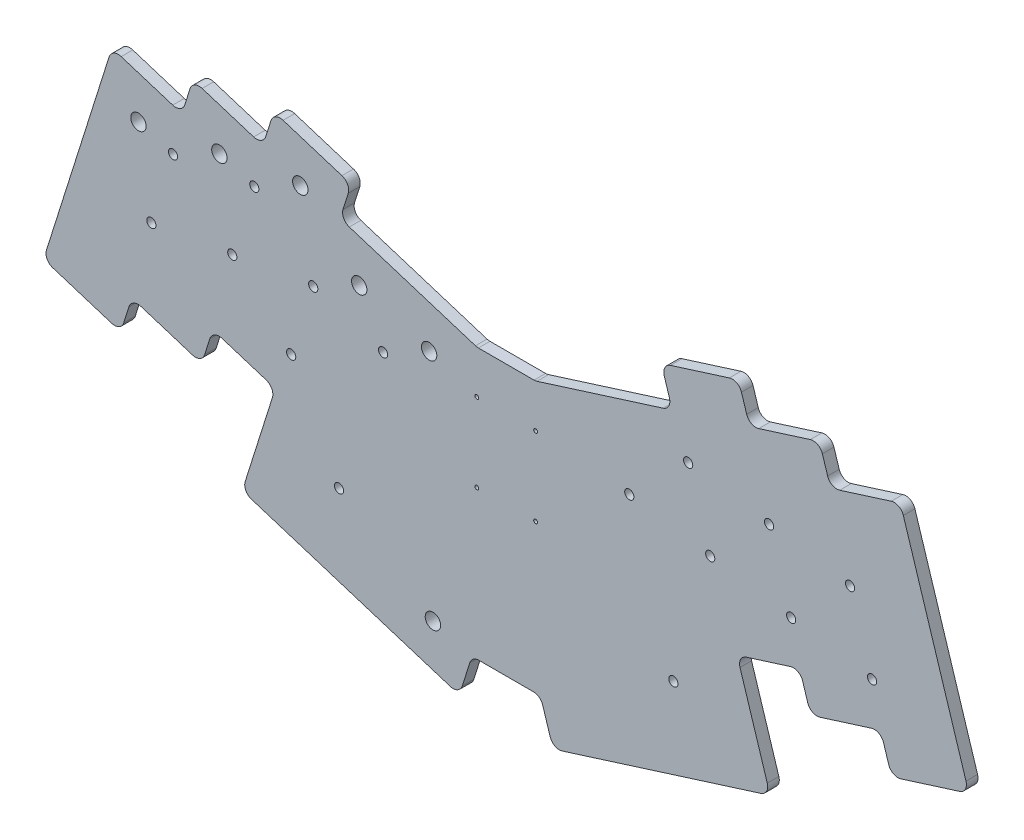
SolidWorks part; units mm, degrees
ref_plane "Front Plane" through (0, 0, 0) normal (0, 0, 1) x (1, 0, 0)
ref_plane "Top Plane" through (0, 0, 0) normal (0, 1, 0) x (1, 0, 0)
ref_plane "Right Plane" through (0, 0, 0) normal (1, 0, 0) x (0, 0, -1)
sketch "Sketch1" plane through (0, 0, 0) normal (0, 0, 1) x (1, 0, 0)
  line L68 (104.9688, -55.7943) -> (103.6157, -60.086)
  line L69 (100.4796, -61.7186) -> (87.1276, -57.5087)
  line L70 (83.9915, -59.1412) -> (82.6383, -63.4329)
  line L71 (79.5023, -65.0655) -> (66.1502, -60.8556)
  line L72 (63.0142, -62.4881) -> (46.7761, -113.9888)
  line L73 (48.4086, -117.1249) -> (63.6681, -121.9362)
  line L74 (66.8041, -120.3036) -> (68.1573, -116.0119)
  line L75 (71.2933, -114.3794) -> (84.6454, -118.5893)
  line L76 (87.7814, -116.9568) -> (89.1346, -112.665)
  line L77 (92.2707, -111.0325) -> (103.7153, -114.641)
  line L78 (105.3478, -117.777) -> (98.2812, -140.1894)
  line L79 (99.9137, -143.3254) -> (151.4145, -159.5635)
  line L80 (154.5505, -157.931) -> (156.4998, -151.7488)
  line L81 (158.884, -150.0006) -> (173.0002, -150.0006)
  line L82 (175.3845, -151.7488) -> (177.3338, -157.931)
  line L83 (180.4698, -159.5635) -> (231.9705, -143.3254)
  line L84 (233.6031, -140.1894) -> (226.5365, -117.777)
  line L85 (228.169, -114.641) -> (239.6136, -111.0325)
  line L86 (242.7497, -112.665) -> (244.1028, -116.9567)
  line L87 (247.2389, -118.5893) -> (260.5909, -114.3794)
  line L88 (263.727, -116.0119) -> (265.0802, -120.3037)
  line L89 (268.2162, -121.9362) -> (283.4757, -117.1249)
  line L90 (285.1082, -113.9888) -> (268.8701, -62.4881)
  line L91 (265.734, -60.8556) -> (252.382, -65.0655)
  line L92 (249.246, -63.4329) -> (247.8928, -59.1412)
  line L93 (244.7567, -57.5087) -> (231.4047, -61.7186)
  line L94 (228.2686, -60.086) -> (226.9154, -55.7943)
  line L95 (223.7794, -54.1618) -> (208.5199, -58.9731)
  line L96 (206.8874, -62.1091) -> (208.2406, -66.4009)
  line L97 (206.608, -69.5369) -> (173.9081, -79.8472)
  line L98 (173.1564, -79.9629) -> (158.7279, -79.9629)
  line L99 (157.9761, -79.8472) -> (125.2762, -69.5369)
  line L100 (123.6437, -66.4009) -> (124.9969, -62.1091)
  line L101 (123.3644, -58.9731) -> (108.1049, -54.1618)
  circle A26 centre (260.7715, -103.3129) radius 1.1906
  circle A27 centre (255.0581, -85.1923) radius 1.1906
  circle A28 centre (239.7942, -99.966) radius 1.1906
  circle A29 centre (234.0808, -81.8454) radius 1.1906
  circle A30 centre (218.8169, -96.6191) radius 1.1906
  circle A31 centre (213.1035, -78.4985) radius 1.1906
  circle A32 centre (197.8395, -93.2722) radius 1.1906
  circle A33 centre (209.2664, -129.5134) radius 1.1906
  arc A68 (108.1049, -54.1618) -> (104.9688, -55.7943) centre (107.3531, -56.546) ccw
  arc A69 (100.4796, -61.7186) -> (103.6157, -60.086) centre (101.2314, -59.3343) ccw
  arc A70 (87.1276, -57.5087) -> (83.9915, -59.1412) centre (86.3757, -59.8929) ccw
  arc A71 (79.5023, -65.0655) -> (82.6383, -63.4329) centre (80.254, -62.6811) ccw
  arc A72 (66.1502, -60.8556) -> (63.0142, -62.4881) centre (65.3985, -63.2399) ccw
  arc A73 (46.7761, -113.9888) -> (48.4086, -117.1249) centre (49.1603, -114.7406) ccw
  arc A74 (63.6681, -121.9362) -> (66.8041, -120.3036) centre (64.4199, -119.552) ccw
  arc A75 (71.2933, -114.3794) -> (68.1573, -116.0119) centre (70.5416, -116.7637) ccw
  arc A76 (84.6454, -118.5893) -> (87.7814, -116.9568) centre (85.3972, -116.2051) ccw
  arc A77 (92.2707, -111.0325) -> (89.1346, -112.665) centre (91.5189, -113.4168) ccw
  arc A78 (105.3478, -117.777) -> (103.7153, -114.641) centre (102.9635, -117.0253) ccw
  arc A79 (98.2812, -140.1894) -> (99.9137, -143.3254) centre (100.6655, -140.9411) ccw
  arc A80 (151.4145, -159.5635) -> (154.5505, -157.931) centre (152.1662, -157.1792) ccw
  arc A81 (158.884, -150.0006) -> (156.4998, -151.7488) centre (158.884, -152.5005) ccw
  arc A82 (175.3845, -151.7488) -> (173.0002, -150.0006) centre (173.0002, -152.5006) ccw
  arc A83 (177.3338, -157.931) -> (180.4698, -159.5635) centre (179.718, -157.1793) ccw
  arc A84 (231.9705, -143.3254) -> (233.6031, -140.1894) centre (231.2188, -140.9411) ccw
  arc A85 (228.169, -114.641) -> (226.5365, -117.777) centre (228.9207, -117.0252) ccw
  arc A86 (242.7497, -112.665) -> (239.6136, -111.0325) centre (240.3653, -113.4169) ccw
  arc A87 (244.1028, -116.9567) -> (247.2389, -118.5893) centre (246.4871, -116.205) ccw
  arc A88 (263.727, -116.0119) -> (260.5909, -114.3794) centre (261.3427, -116.7636) ccw
  arc A89 (265.0802, -120.3037) -> (268.2162, -121.9362) centre (267.4644, -119.5519) ccw
  arc A90 (283.4757, -117.1249) -> (285.1082, -113.9888) centre (282.724, -114.7406) ccw
  arc A91 (268.8701, -62.4881) -> (265.734, -60.8556) centre (266.4858, -63.2399) ccw
  arc A92 (249.246, -63.4329) -> (252.382, -65.0655) centre (251.6302, -62.6813) ccw
  arc A93 (247.8928, -59.1412) -> (244.7567, -57.5087) centre (245.5085, -59.8929) ccw
  arc A94 (228.2686, -60.086) -> (231.4047, -61.7186) centre (230.6529, -59.3343) ccw
  arc A95 (226.9154, -55.7943) -> (223.7794, -54.1618) centre (224.5311, -56.5462) ccw
  arc A96 (208.5199, -58.9731) -> (206.8874, -62.1091) centre (209.2716, -61.3573) ccw
  arc A97 (206.608, -69.5369) -> (208.2406, -66.4009) centre (205.8563, -67.1526) ccw
  arc A98 (173.1564, -79.9629) -> (173.9081, -79.8472) centre (173.1564, -77.4632) ccw
  arc A99 (157.9761, -79.8472) -> (158.7279, -79.9629) centre (158.7279, -77.4627) ccw
  arc A100 (123.6437, -66.4009) -> (125.2762, -69.5369) centre (126.028, -67.1526) ccw
  arc A101 (124.9969, -62.1091) -> (123.3644, -58.9731) centre (122.6126, -61.3574) ccw
  circle A102 centre (122.6179, -129.5134) radius 1.1906
  circle A103 centre (134.0447, -93.2722) radius 1.1906
  circle A104 centre (110.2107, -105.6794) radius 1.1906
  circle A105 centre (115.9241, -87.5588) radius 1.1906
  circle A106 centre (100.6602, -72.7851) radius 1.1906
  circle A107 centre (94.9468, -90.9057) radius 1.1906
  circle A108 centre (73.9695, -94.2526) radius 1.1906
  circle A109 centre (79.584, -76.0437) radius 1.1906
  circle A110 centre (146.9421, -147.1439) radius 1.9939
  circle A111 centre (145.9617, -87.0686) radius 1.9939
  circle A112 centre (127.8411, -81.3552) radius 1.9939
  circle A113 centre (112.5772, -66.5815) radius 1.9939
  circle A114 centre (91.5999, -69.9284) radius 1.9939
  circle A115 centre (70.6226, -73.2753) radius 1.9939
  circle A116 centre (158.3221, -111.4786) radius 0.5
  circle A117 centre (173.5621, -111.4786) radius 0.5
  circle A118 centre (173.5621, -91.1586) radius 0.5
  circle A119 centre (158.3221, -91.1586) radius 0.5
extrude "Boss-Extrude1" add sketch "Sketch1" along normal blind 3
sketch "Sketch2" plane through (0, 0, 0) normal (0, 0, -1) x (-1, 0, 0)
  line L0 (-109.6085, -49.3932) -> (-124.8679, -54.2045)
  line L1 (-129.7655, -63.6126) -> (-129.1641, -65.5201)
  line L2 (-129.1641, -65.5201) -> (-159.1127, -74.9629)
  line L3 (-159.1127, -74.9629) -> (-172.7716, -74.9629)
  line L4 (-172.7716, -74.9629) -> (-202.7202, -65.5201)
  line L5 (-202.7202, -65.5201) -> (-202.1188, -63.6127)
  line L6 (-207.0165, -54.2045) -> (-222.2759, -49.3932)
  line L7 (-231.684, -54.2907) -> (-232.2854, -56.1982)
  line L8 (-232.2854, -56.1982) -> (-243.2531, -52.7401)
  line L9 (-252.6614, -57.6377) -> (-253.2628, -59.5451)
  line L10 (-253.2628, -59.5451) -> (-264.2305, -56.087)
  line L11 (-273.6387, -60.9846) -> (-289.8768, -112.4852)
  line L12 (-284.9792, -121.8935) -> (-269.7198, -126.7048)
  line L13 (-260.3116, -121.8071) -> (-259.7102, -119.8997)
  line L14 (-259.7102, -119.8997) -> (-248.7424, -123.3579)
  line L15 (-239.3342, -118.4603) -> (-238.7328, -116.5528)
  line L16 (-238.7328, -116.5528) -> (-232.0568, -118.6578)
  line L17 (-232.0568, -118.6578) -> (-238.3716, -138.6858)
  line L18 (-233.4741, -148.094) -> (-181.9734, -164.3321)
  line L19 (-172.5652, -159.4345) -> (-171.1671, -155.0006)
  line L20 (-171.1671, -155.0006) -> (-160.7171, -155.0006)
  line L21 (-160.7171, -155.0006) -> (-159.3191, -159.4345)
  line L22 (-149.9109, -164.3321) -> (-98.4102, -148.094)
  line L23 (-93.5126, -138.6858) -> (-99.8275, -118.6578)
  line L24 (-99.8275, -118.6578) -> (-93.1514, -116.5528)
  line L25 (-93.1514, -116.5528) -> (-92.5501, -118.4602)
  line L26 (-83.1418, -123.3578) -> (-72.1741, -119.8997)
  line L27 (-72.1741, -119.8997) -> (-71.5727, -121.8071)
  line L28 (-62.1645, -126.7047) -> (-46.9051, -121.8935)
  line L29 (-42.0075, -112.4853) -> (-58.2456, -60.9846)
  line L30 (-67.6538, -56.087) -> (-78.6215, -59.5451)
  line L31 (-78.6215, -59.5451) -> (-79.2229, -57.6378)
  line L32 (-88.6312, -52.7401) -> (-99.5988, -56.1982)
  line L33 (-99.5988, -56.1982) -> (-100.2002, -54.2909)
  line L34 (-108.1049, -54.1618) -> (-123.3644, -58.9731)
  line L35 (-124.9969, -62.1091) -> (-123.6437, -66.4009)
  line L36 (-125.2762, -69.5369) -> (-157.9761, -79.8472)
  line L37 (-158.7279, -79.9629) -> (-173.1564, -79.9629)
  line L38 (-173.9081, -79.8472) -> (-206.608, -69.5369)
  line L39 (-208.2406, -66.4009) -> (-206.8874, -62.1091)
  line L40 (-208.5199, -58.9731) -> (-223.7794, -54.1618)
  line L41 (-226.9154, -55.7943) -> (-228.2686, -60.086)
  line L42 (-231.4047, -61.7186) -> (-244.7567, -57.5087)
  line L43 (-247.8928, -59.1412) -> (-249.246, -63.4329)
  line L44 (-252.382, -65.0655) -> (-265.734, -60.8556)
  line L45 (-268.8701, -62.4881) -> (-285.1082, -113.9888)
  line L46 (-283.4757, -117.1249) -> (-268.2162, -121.9362)
  line L47 (-265.0802, -120.3037) -> (-263.727, -116.0119)
  line L48 (-260.5909, -114.3794) -> (-247.2389, -118.5893)
  line L49 (-244.1028, -116.9567) -> (-242.7497, -112.665)
  line L50 (-239.6136, -111.0325) -> (-228.169, -114.641)
  line L51 (-226.5365, -117.777) -> (-233.6031, -140.1894)
  line L52 (-231.9705, -143.3254) -> (-180.4698, -159.5635)
  line L53 (-177.3338, -157.931) -> (-175.3845, -151.7488)
  line L54 (-173.0002, -150.0006) -> (-158.884, -150.0006)
  line L55 (-156.4998, -151.7488) -> (-154.5505, -157.931)
  line L56 (-151.4145, -159.5635) -> (-99.9137, -143.3254)
  line L57 (-98.2812, -140.1894) -> (-105.3478, -117.777)
  line L58 (-103.7153, -114.641) -> (-92.2707, -111.0325)
  line L59 (-89.1346, -112.665) -> (-87.7814, -116.9568)
  line L60 (-84.6454, -118.5893) -> (-71.2933, -114.3794)
  line L61 (-68.1573, -116.0119) -> (-66.8041, -120.3036)
  line L62 (-63.6681, -121.9362) -> (-48.4086, -117.1249)
  line L63 (-46.7761, -113.9888) -> (-63.0142, -62.4881)
  line L64 (-66.1502, -60.8556) -> (-79.5023, -65.0655)
  line L65 (-82.6383, -63.4329) -> (-83.9915, -59.1412)
  line L66 (-87.1276, -57.5087) -> (-100.4796, -61.7186)
  line L67 (-103.6157, -60.086) -> (-104.9688, -55.7943)
  line L68 (-108.1049, -54.1618) -> (-123.3644, -58.9731)
  line L69 (-124.9969, -62.1091) -> (-123.6437, -66.4009)
  line L70 (-125.2762, -69.5369) -> (-157.9761, -79.8472)
  line L71 (-158.7279, -79.9629) -> (-173.1564, -79.9629)
  line L72 (-173.9081, -79.8472) -> (-206.608, -69.5369)
  line L73 (-208.2406, -66.4009) -> (-206.8874, -62.1091)
  line L74 (-208.5199, -58.9731) -> (-223.7794, -54.1618)
  line L75 (-226.9154, -55.7943) -> (-228.2686, -60.086)
  line L76 (-231.4047, -61.7186) -> (-244.7567, -57.5087)
  line L77 (-247.8928, -59.1412) -> (-249.246, -63.4329)
  line L78 (-252.382, -65.0655) -> (-265.734, -60.8556)
  line L79 (-268.8701, -62.4881) -> (-285.1082, -113.9888)
  line L80 (-283.4757, -117.1249) -> (-268.2162, -121.9362)
  line L81 (-265.0802, -120.3037) -> (-263.727, -116.0119)
  line L82 (-260.5909, -114.3794) -> (-247.2389, -118.5893)
  line L83 (-244.1028, -116.9567) -> (-242.7497, -112.665)
  line L84 (-239.6136, -111.0325) -> (-228.169, -114.641)
  line L85 (-226.5365, -117.777) -> (-233.6031, -140.1894)
  line L86 (-231.9705, -143.3254) -> (-180.4698, -159.5635)
  line L87 (-177.3338, -157.931) -> (-175.3845, -151.7488)
  line L88 (-173.0002, -150.0006) -> (-158.884, -150.0006)
  line L89 (-156.4998, -151.7488) -> (-154.5505, -157.931)
  line L90 (-151.4145, -159.5635) -> (-99.9137, -143.3254)
  line L91 (-98.2812, -140.1894) -> (-105.3478, -117.777)
  line L92 (-103.7153, -114.641) -> (-92.2707, -111.0325)
  line L93 (-89.1346, -112.665) -> (-87.7814, -116.9568)
  line L94 (-84.6454, -118.5893) -> (-71.2933, -114.3794)
  line L95 (-68.1573, -116.0119) -> (-66.8041, -120.3036)
  line L96 (-63.6681, -121.9362) -> (-48.4086, -117.1249)
  line L97 (-46.7761, -113.9888) -> (-63.0142, -62.4881)
  line L98 (-66.1502, -60.8556) -> (-79.5023, -65.0655)
  line L99 (-82.6383, -63.4329) -> (-83.9915, -59.1412)
  line L100 (-87.1276, -57.5087) -> (-100.4796, -61.7186)
  line L101 (-103.6157, -60.086) -> (-104.9688, -55.7943)
  arc A0 (-124.8679, -54.2045) -> (-129.7655, -63.6126) centre (-122.6126, -61.3574) ccw
  arc A1 (-129.1641, -65.5201) -> (-129.1641, -65.5201) centre (-129.1641, -65.5201) ccw
  arc A2 (-159.1127, -74.9629) -> (-159.1127, -74.9629) centre (-159.1127, -74.9629) ccw
  arc A3 (-172.7716, -74.9629) -> (-172.7716, -74.9629) centre (-172.7716, -74.9629) ccw
  arc A4 (-202.7202, -65.5201) -> (-202.7202, -65.5201) centre (-202.7202, -65.5201) ccw
  arc A5 (-202.1188, -63.6127) -> (-207.0165, -54.2045) centre (-209.2716, -61.3573) ccw
  arc A6 (-222.2759, -49.3932) -> (-231.684, -54.2907) centre (-224.5311, -56.5462) ccw
  arc A7 (-232.2854, -56.1982) -> (-232.2854, -56.1982) centre (-232.2854, -56.1982) ccw
  arc A8 (-243.2531, -52.7401) -> (-252.6614, -57.6377) centre (-245.5085, -59.8929) ccw
  arc A9 (-253.2628, -59.5451) -> (-253.2628, -59.5451) centre (-253.2628, -59.5451) ccw
  arc A10 (-264.2305, -56.087) -> (-273.6387, -60.9846) centre (-266.4858, -63.2399) ccw
  arc A11 (-289.8768, -112.4852) -> (-284.9792, -121.8935) centre (-282.724, -114.7406) ccw
  arc A12 (-269.7198, -126.7048) -> (-260.3116, -121.8071) centre (-267.4644, -119.5519) ccw
  arc A13 (-259.7102, -119.8997) -> (-259.7102, -119.8997) centre (-259.7102, -119.8997) ccw
  arc A14 (-248.7424, -123.3579) -> (-239.3342, -118.4603) centre (-246.4871, -116.205) ccw
  arc A15 (-238.7328, -116.5528) -> (-238.7328, -116.5528) centre (-238.7328, -116.5528) ccw
  arc A16 (-232.0568, -118.6578) -> (-232.0568, -118.6578) centre (-232.0568, -118.6578) ccw
  arc A17 (-238.3716, -138.6858) -> (-233.4741, -148.094) centre (-231.2188, -140.9411) ccw
  arc A18 (-181.9734, -164.3321) -> (-172.5652, -159.4345) centre (-179.718, -157.1793) ccw
  arc A19 (-171.1671, -155.0006) -> (-171.1671, -155.0006) centre (-171.1671, -155.0006) ccw
  arc A20 (-160.7171, -155.0006) -> (-160.7171, -155.0006) centre (-160.7171, -155.0006) ccw
  arc A21 (-159.3191, -159.4345) -> (-149.9109, -164.3321) centre (-152.1662, -157.1792) ccw
  arc A22 (-98.4102, -148.094) -> (-93.5126, -138.6858) centre (-100.6655, -140.9411) ccw
  arc A23 (-99.8275, -118.6578) -> (-99.8275, -118.6578) centre (-99.8275, -118.6578) ccw
  arc A24 (-93.1514, -116.5528) -> (-93.1514, -116.5528) centre (-93.1514, -116.5528) ccw
  arc A25 (-92.5501, -118.4602) -> (-83.1418, -123.3578) centre (-85.3972, -116.2051) ccw
  arc A26 (-72.1741, -119.8997) -> (-72.1741, -119.8997) centre (-72.1741, -119.8997) ccw
  arc A27 (-71.5727, -121.8071) -> (-62.1645, -126.7047) centre (-64.4199, -119.552) ccw
  arc A28 (-46.9051, -121.8935) -> (-42.0075, -112.4853) centre (-49.1603, -114.7406) ccw
  arc A29 (-58.2456, -60.9846) -> (-67.6538, -56.087) centre (-65.3985, -63.2399) ccw
  arc A30 (-78.6215, -59.5451) -> (-78.6215, -59.5451) centre (-78.6215, -59.5451) ccw
  arc A31 (-79.2229, -57.6378) -> (-88.6312, -52.7401) centre (-86.3757, -59.8929) ccw
  arc A32 (-99.5988, -56.1982) -> (-99.5988, -56.1982) centre (-99.5988, -56.1982) ccw
  arc A33 (-100.2002, -54.2909) -> (-109.6085, -49.3932) centre (-107.3531, -56.546) ccw
  arc A34 (-104.9688, -55.7943) -> (-108.1049, -54.1618) centre (-107.3531, -56.546) ccw
  arc A35 (-123.3644, -58.9731) -> (-124.9969, -62.1091) centre (-122.6126, -61.3574) ccw
  arc A36 (-125.2762, -69.5369) -> (-123.6437, -66.4009) centre (-126.028, -67.1526) ccw
  arc A37 (-158.7279, -79.9629) -> (-157.9761, -79.8472) centre (-158.7279, -77.4627) ccw
  arc A38 (-173.9081, -79.8472) -> (-173.1564, -79.9629) centre (-173.1564, -77.4632) ccw
  arc A39 (-208.2406, -66.4009) -> (-206.608, -69.5369) centre (-205.8563, -67.1526) ccw
  arc A40 (-206.8874, -62.1091) -> (-208.5199, -58.9731) centre (-209.2716, -61.3573) ccw
  arc A41 (-223.7794, -54.1618) -> (-226.9154, -55.7943) centre (-224.5311, -56.5462) ccw
  arc A42 (-231.4047, -61.7186) -> (-228.2686, -60.086) centre (-230.6529, -59.3343) ccw
  arc A43 (-244.7567, -57.5087) -> (-247.8928, -59.1412) centre (-245.5085, -59.8929) ccw
  arc A44 (-252.382, -65.0655) -> (-249.246, -63.4329) centre (-251.6302, -62.6813) ccw
  arc A45 (-265.734, -60.8556) -> (-268.8701, -62.4881) centre (-266.4858, -63.2399) ccw
  arc A46 (-285.1082, -113.9888) -> (-283.4757, -117.1249) centre (-282.724, -114.7406) ccw
  arc A47 (-268.2162, -121.9362) -> (-265.0802, -120.3037) centre (-267.4644, -119.5519) ccw
  arc A48 (-260.5909, -114.3794) -> (-263.727, -116.0119) centre (-261.3427, -116.7636) ccw
  arc A49 (-247.2389, -118.5893) -> (-244.1028, -116.9567) centre (-246.4871, -116.205) ccw
  arc A50 (-239.6136, -111.0325) -> (-242.7497, -112.665) centre (-240.3653, -113.4169) ccw
  arc A51 (-226.5365, -117.777) -> (-228.169, -114.641) centre (-228.9207, -117.0252) ccw
  arc A52 (-233.6031, -140.1894) -> (-231.9705, -143.3254) centre (-231.2188, -140.9411) ccw
  arc A53 (-180.4698, -159.5635) -> (-177.3338, -157.931) centre (-179.718, -157.1793) ccw
  arc A54 (-173.0002, -150.0006) -> (-175.3845, -151.7488) centre (-173.0002, -152.5006) ccw
  arc A55 (-156.4998, -151.7488) -> (-158.884, -150.0006) centre (-158.884, -152.5005) ccw
  arc A56 (-154.5505, -157.931) -> (-151.4145, -159.5635) centre (-152.1662, -157.1792) ccw
  arc A57 (-99.9137, -143.3254) -> (-98.2812, -140.1894) centre (-100.6655, -140.9411) ccw
  arc A58 (-103.7153, -114.641) -> (-105.3478, -117.777) centre (-102.9635, -117.0253) ccw
  arc A59 (-89.1346, -112.665) -> (-92.2707, -111.0325) centre (-91.5189, -113.4168) ccw
  arc A60 (-87.7814, -116.9568) -> (-84.6454, -118.5893) centre (-85.3972, -116.2051) ccw
  arc A61 (-68.1573, -116.0119) -> (-71.2933, -114.3794) centre (-70.5416, -116.7637) ccw
  arc A62 (-66.8041, -120.3036) -> (-63.6681, -121.9362) centre (-64.4199, -119.552) ccw
  arc A63 (-48.4086, -117.1249) -> (-46.7761, -113.9888) centre (-49.1603, -114.7406) ccw
  arc A64 (-63.0142, -62.4881) -> (-66.1502, -60.8556) centre (-65.3985, -63.2399) ccw
  arc A65 (-82.6383, -63.4329) -> (-79.5023, -65.0655) centre (-80.254, -62.6811) ccw
  arc A66 (-83.9915, -59.1412) -> (-87.1276, -57.5087) centre (-86.3757, -59.8929) ccw
  arc A67 (-103.6157, -60.086) -> (-100.4796, -61.7186) centre (-101.2314, -59.3343) ccw
  arc A68 (-104.9688, -55.7943) -> (-108.1049, -54.1618) centre (-107.3531, -56.546) ccw
  arc A69 (-123.3644, -58.9731) -> (-124.9969, -62.1091) centre (-122.6126, -61.3574) ccw
  arc A70 (-125.2762, -69.5369) -> (-123.6437, -66.4009) centre (-126.028, -67.1526) ccw
  arc A71 (-158.7279, -79.9629) -> (-157.9761, -79.8472) centre (-158.7279, -77.4627) ccw
  arc A72 (-173.9081, -79.8472) -> (-173.1564, -79.9629) centre (-173.1564, -77.4632) ccw
  arc A73 (-208.2406, -66.4009) -> (-206.608, -69.5369) centre (-205.8563, -67.1526) ccw
  arc A74 (-206.8874, -62.1091) -> (-208.5199, -58.9731) centre (-209.2716, -61.3573) ccw
  arc A75 (-223.7794, -54.1618) -> (-226.9154, -55.7943) centre (-224.5311, -56.5462) ccw
  arc A76 (-231.4047, -61.7186) -> (-228.2686, -60.086) centre (-230.6529, -59.3343) ccw
  arc A77 (-244.7567, -57.5087) -> (-247.8928, -59.1412) centre (-245.5085, -59.8929) ccw
  arc A78 (-252.382, -65.0655) -> (-249.246, -63.4329) centre (-251.6302, -62.6813) ccw
  arc A79 (-265.734, -60.8556) -> (-268.8701, -62.4881) centre (-266.4858, -63.2399) ccw
  arc A80 (-285.1082, -113.9888) -> (-283.4757, -117.1249) centre (-282.724, -114.7406) ccw
  arc A81 (-268.2162, -121.9362) -> (-265.0802, -120.3037) centre (-267.4644, -119.5519) ccw
  arc A82 (-260.5909, -114.3794) -> (-263.727, -116.0119) centre (-261.3427, -116.7636) ccw
  arc A83 (-247.2389, -118.5893) -> (-244.1028, -116.9567) centre (-246.4871, -116.205) ccw
  arc A84 (-239.6136, -111.0325) -> (-242.7497, -112.665) centre (-240.3653, -113.4169) ccw
  arc A85 (-226.5365, -117.777) -> (-228.169, -114.641) centre (-228.9207, -117.0252) ccw
  arc A86 (-233.6031, -140.1894) -> (-231.9705, -143.3254) centre (-231.2188, -140.9411) ccw
  arc A87 (-180.4698, -159.5635) -> (-177.3338, -157.931) centre (-179.718, -157.1793) ccw
  arc A88 (-173.0002, -150.0006) -> (-175.3845, -151.7488) centre (-173.0002, -152.5006) ccw
  arc A89 (-156.4998, -151.7488) -> (-158.884, -150.0006) centre (-158.884, -152.5005) ccw
  arc A90 (-154.5505, -157.931) -> (-151.4145, -159.5635) centre (-152.1662, -157.1792) ccw
  arc A91 (-99.9137, -143.3254) -> (-98.2812, -140.1894) centre (-100.6655, -140.9411) ccw
  arc A92 (-103.7153, -114.641) -> (-105.3478, -117.777) centre (-102.9635, -117.0253) ccw
  arc A93 (-89.1346, -112.665) -> (-92.2707, -111.0325) centre (-91.5189, -113.4168) ccw
  arc A94 (-87.7814, -116.9568) -> (-84.6454, -118.5893) centre (-85.3972, -116.2051) ccw
  arc A95 (-68.1573, -116.0119) -> (-71.2933, -114.3794) centre (-70.5416, -116.7637) ccw
  arc A96 (-66.8041, -120.3036) -> (-63.6681, -121.9362) centre (-64.4199, -119.552) ccw
  arc A97 (-48.4086, -117.1249) -> (-46.7761, -113.9888) centre (-49.1603, -114.7406) ccw
  arc A98 (-63.0142, -62.4881) -> (-66.1502, -60.8556) centre (-65.3985, -63.2399) ccw
  arc A99 (-82.6383, -63.4329) -> (-79.5023, -65.0655) centre (-80.254, -62.6811) ccw
  arc A100 (-83.9915, -59.1412) -> (-87.1276, -57.5087) centre (-86.3757, -59.8929) ccw
  arc A101 (-103.6157, -60.086) -> (-100.4796, -61.7186) centre (-101.2314, -59.3343) ccw
  dimension "D1" = 0
  dimension "D2" = 5
